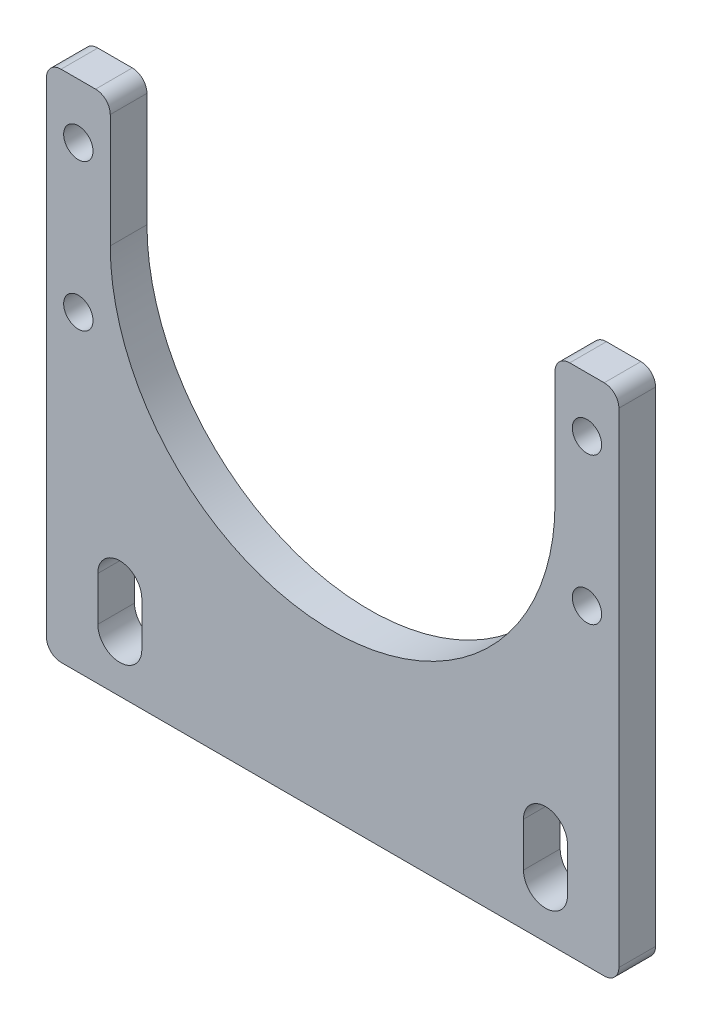
SolidWorks part; units mm, degrees
ref_plane "前视基准面" through (0, 0, 0) normal (0, 0, 1) x (1, 0, 0)
ref_plane "上视基准面" through (0, 0, 0) normal (0, 1, 0) x (1, 0, 0)
ref_plane "右视基准面" through (0, 0, 0) normal (1, 0, 0) x (0, 0, -1)
sketch "草图1" plane through (0, 0, 0) normal (0, 0, 1) x (1, 0, 0)
  line L0 (0, 94.6757) -> (0, 59) construction
  line L3 (-39, -23.5) -> (39, -23.5)
  line L6 (-39, -23.5) -> (0, 0) construction
  line L7 (-32, -10.5) -> (-32, -16.5)
  line L8 (-26, -10.5) -> (-26, -16.5)
  line L9 (26, -10.5) -> (26, -16.5)
  line L10 (32, -10.5) -> (32, -16.5)
  line L12 (0, 0) -> (39, -23.5) construction
  line L14 (0, 0) -> (0, -94.3835) construction
  line L18 (-39, 29) -> (-30.3, 29)
  line L19 (-39, -23.5) -> (-39, 46.5)
  line L20 (-30.3, 29) -> (-30.3, 46.5)
  line L21 (-39, 46.5) -> (-30.3, 46.5)
  line L22 (-34.65, 46.5) -> (-34.65, 20.5961) construction
  line L23 (30.3, 29) -> (30.3, 46.5)
  line L24 (39, 46.5) -> (30.3, 46.5)
  line L25 (39, -23.5) -> (39, 46.5)
  line L26 (30.3, 29) -> (39, 29)
  arc A0 (-32, -16.5) -> (-26, -16.5) centre (-29, -16.5) ccw
  arc A1 (-26, -10.5) -> (-32, -10.5) centre (-29, -10.5) ccw
  arc A2 (26, -10.5) -> (32, -10.5) centre (29, -10.5) cw
  arc A3 (32, -16.5) -> (26, -16.5) centre (29, -16.5) cw
  arc A6 (-30.3, 29) -> (30.3, 29) centre (0, 29) ccw
  circle A7 centre (-34.65, 39) radius 2
  circle A8 centre (-34.65, 19) radius 2
  circle A9 centre (34.65, 19) radius 2
  circle A10 centre (34.65, 39) radius 2
  point P0 (0, 0)
  point P4 (0, -23.5)
  dimension "D1" = 6
  dimension "D2" = 6
  dimension "D7" = 70
  dimension "D5" = 20
  dimension "D3" = 58
  dimension "D4" = 78
  dimension "D6" = 7
extrude "凸台-拉伸1" add sketch "草图1" along normal blind 5
fillet "圆角2" radius 2 6 edges at (39, -23.5, 2.5) (-39, -23.5, 2.5) (39, 46.5, 2.5) (-39, 46.5, 2.5) (30.3, 46.5, 2.5) (-30.3, 46.5, 2.5)
